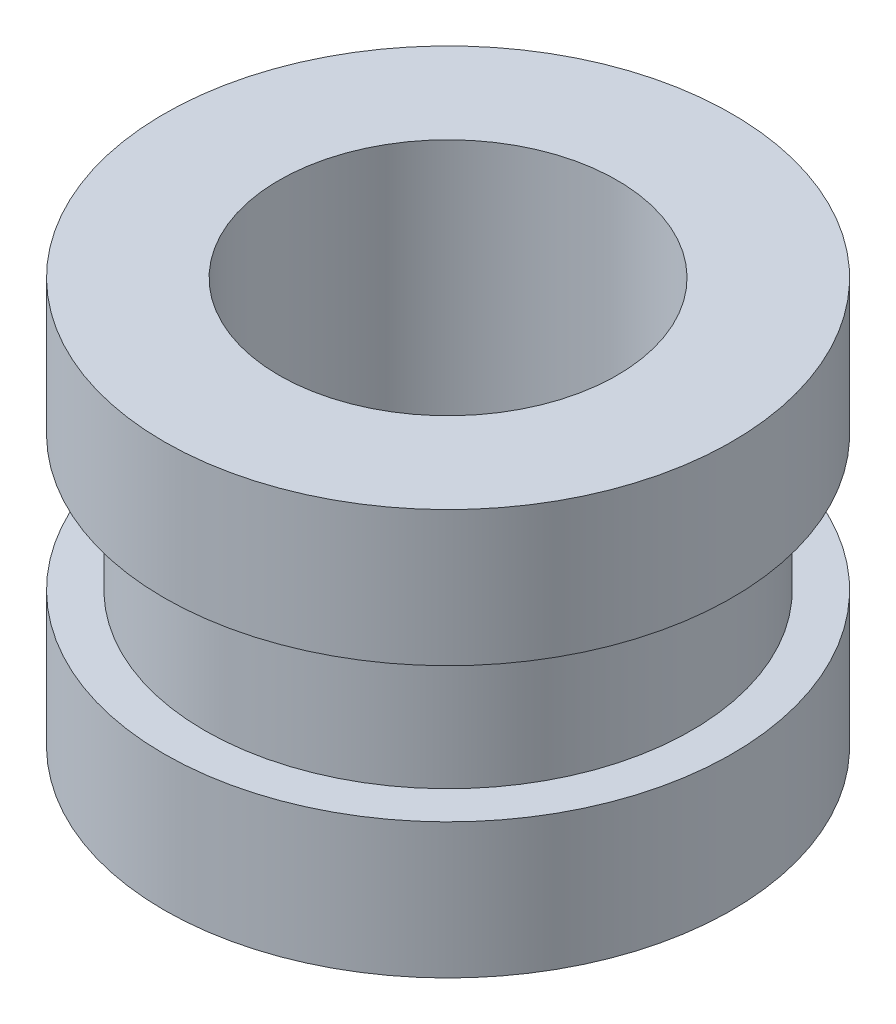
SolidWorks part; units mm, degrees
material "H62"
ref_plane "前视基准面" through (0, 0, 0) normal (0, 0, 1) x (1, 0, 0)
ref_plane "上视基准面" through (0, 0, 0) normal (0, 1, 0) x (1, 0, 0)
ref_plane "右视基准面" through (0, 0, 0) normal (1, 0, 0) x (0, 0, -1)
other "Configuration Table"
sketch "草图1" plane through (0, 0, 0) normal (0, 1, 0) x (1, 0, 0)
  circle A0 centre (0, 0) radius 2.1
  dimension "D1" = 4.2
extrude "凸台-拉伸1" add sketch "草图1" along normal blind 1
sketch "草图2" plane through (0, 1, 0) normal (0, 1, 0) x (1, 0, 0)
  circle A0 centre (0, 0) radius 1.8
  circle A1 centre (0, 0) radius 2.1 construction
  dimension "D1" = 0.3
extrude "凸台-拉伸2" add sketch "草图2" along normal blind 1
sketch "草图3" plane through (0, 2, 0) normal (0, 1, 0) x (1, 0, 0)
  circle A1 centre (0, 0) radius 2.1
  circle A2 centre (0, 0) radius 2.1
  dimension "D1" = 0
extrude "凸台-拉伸3" add sketch "草图3" along normal blind 1
hole_wizard "M3 螺纹孔1" positions "草图4" profile "草图5" tap size "M3" standard "GB" end condition through all
sketch "草图4" plane through (0, 3, 0) normal (0, 1, 0) x (1, 0, 0)
  point P0 (0, 0)
sketch "草图5" plane through (0, 3, 0) normal (1, 0, 0) x (0, 0, 1)
  line L0 (0, 0) -> (0, 3)
  line L1 (0, 3) -> (1.25, 3)
  line L2 (1.25, 3) -> (1.25, 0)
  line L5 (1.25, 0) -> (0, 0)
  line L11 (0, -6.35) -> (0, 107.95) construction
  dimension "通孔螺纹孔钻头直径" = 2.5
  dimension "通孔螺纹孔钻头深度" = 3
cosmetic thread "孔螺蚊线1" parameters "D2"=3
